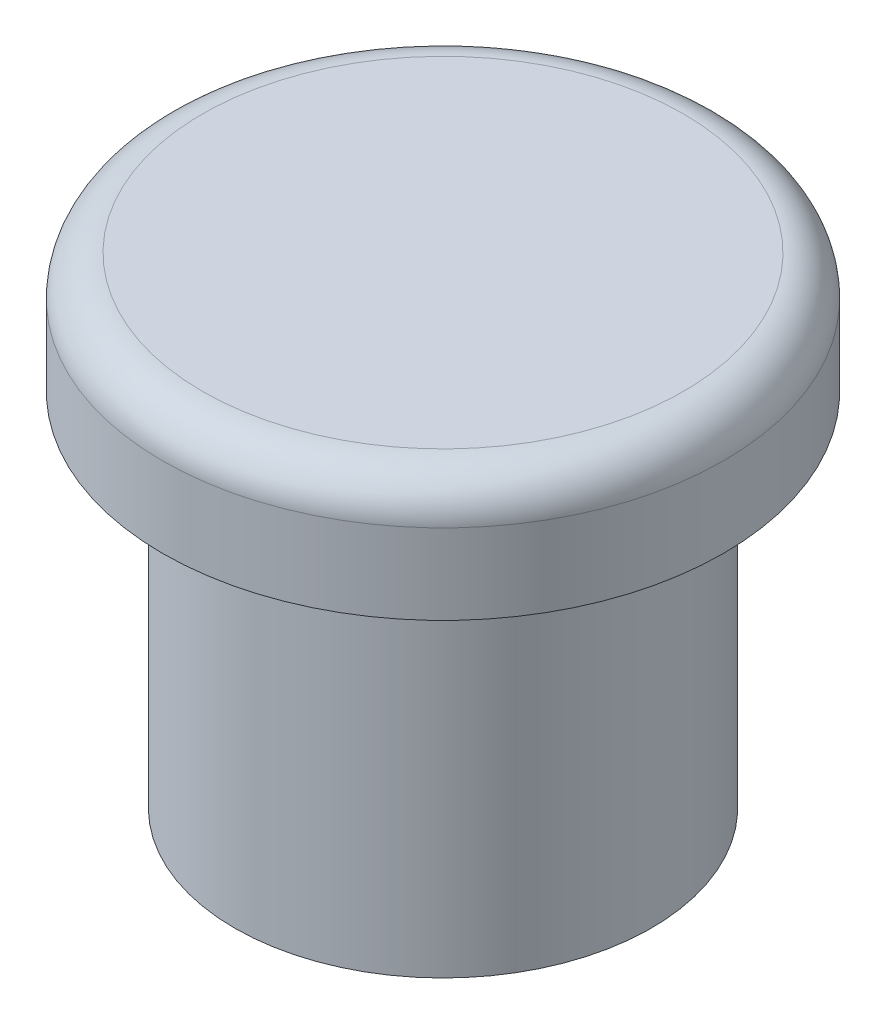
SolidWorks part; units mm, degrees
ref_plane "Front Plane" through (0, 0, 0) normal (0, 0, 1) x (1, 0, 0)
ref_plane "Top Plane" through (0, 0, 0) normal (0, 1, 0) x (1, 0, 0)
ref_plane "Right Plane" through (0, 0, 0) normal (1, 0, 0) x (0, 0, -1)
sketch "Sketch1" plane through (0, 0, 0) normal (0, 1, 0) x (1, 0, 0)
  circle A0 centre (0, 0) radius 1.95
  circle A1 centre (0, 0) radius 2.6
  dimension "D1" = 3.9
  dimension "D2" = 5.2
extrude "Boss-Extrude1" add sketch "Sketch1" along normal blind 4.5
sketch "Sketch2" plane through (0, 4.5, 0) normal (0, 1, 0) x (1, 0, 0)
  circle A0 centre (0, 0) radius 3.5
  dimension "D1" = 7
extrude "Boss-Extrude2" add sketch "Sketch2" along normal blind 1.5
fillet "Fillet1" radius 0.5 1 edges at (0, 6, 3.5)
